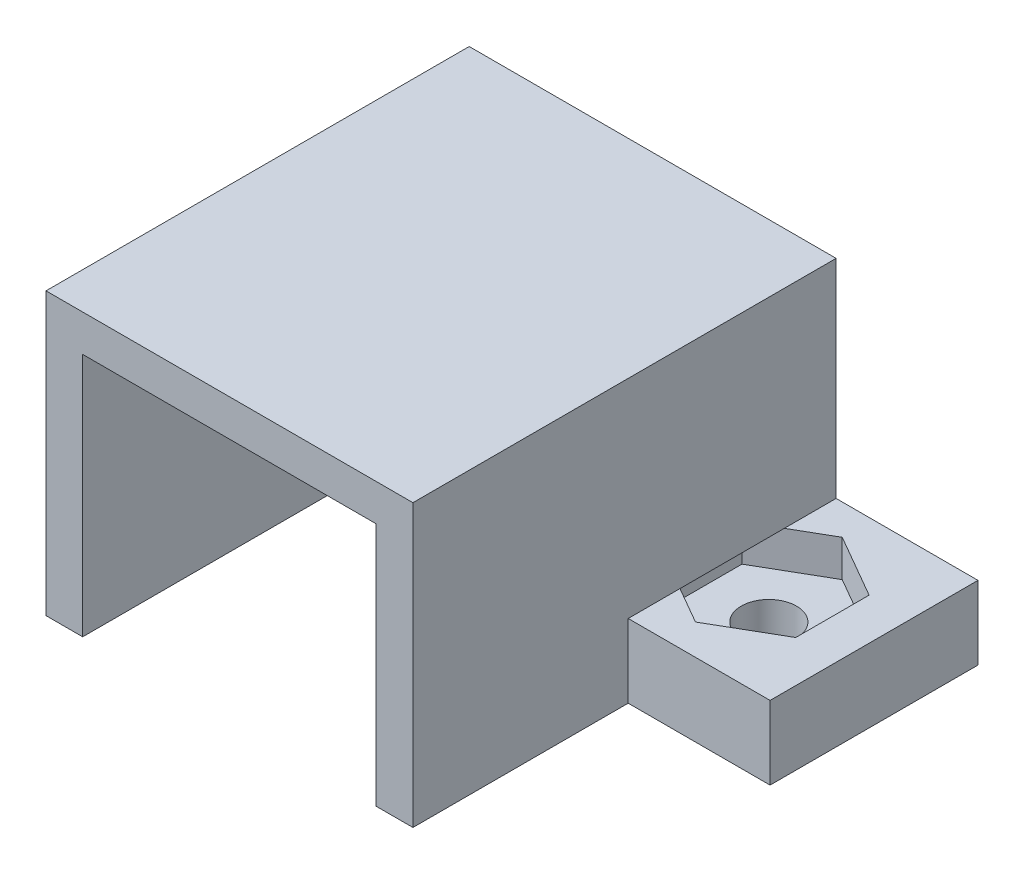
SolidWorks part; units mm, degrees
material "ABS"
ref_plane "Front Plane" through (0, 0, 0) normal (0, 0, 1) x (1, 0, 0)
ref_plane "Top Plane" through (0, 0, 0) normal (0, 1, 0) x (1, 0, 0)
ref_plane "Right Plane" through (0, 0, 0) normal (1, 0, 0) x (0, 0, -1)
sketch "Sketch4" plane through (0, 0, 0) normal (0, 0, 1) x (1, 0, 0)
  line L0 (0, 0) -> (0, 3)
  line L1 (0, 3) -> (5.8, 3)
  line L2 (5.8, 3) -> (5.8, 11.5)
  line L3 (5.8, 11.5) -> (20.8, 11.5)
  line L4 (20.8, 11.5) -> (20.8, 3)
  line L5 (20.8, 3) -> (26.6, 3)
  line L6 (26.6, 3) -> (26.6, 0)
  line L7 (26.6, 0) -> (19.3, 0)
  line L8 (19.3, 0) -> (19.3, 10)
  line L9 (19.3, 10) -> (7.3, 10)
  line L10 (7.3, 10) -> (7.3, 0)
  line L11 (7.3, 0) -> (0, 0)
  dimension "D1" = 5.8
  dimension "D2" = 1.5
  dimension "D3" = 3
  dimension "D4" = 11.5
  dimension "D5" = 1.5
  dimension "D6" = 15
  dimension "D7" = 1.5
extrude "Boss-Extrude4" add sketch "Sketch4" along normal blind 8.5
sketch "Sketch5" plane through (0, 0, 8.5) normal (0, 0, 1) x (1, 0, 0)
  line L0 (7.3, 0) -> (7.3, 10)
  line L1 (7.3, 10) -> (19.3, 10)
  line L2 (19.3, 10) -> (19.3, 0)
  line L3 (19.3, 0) -> (20.8, 0)
  line L4 (19.3, 0) -> (26.6, 0) construction
  line L5 (20.8, 0) -> (20.8, 11.5)
  line L6 (20.8, 11.5) -> (5.8, 11.5)
  line L7 (5.8, 11.5) -> (5.8, 0)
  line L8 (0, 0) -> (7.3, 0) construction
  line L9 (5.8, 0) -> (7.3, 0)
extrude "Boss-Extrude5" add sketch "Sketch5" along normal blind 8.8
sketch "Sketch6" plane through (0, 3, 0) normal (0, 1, 0) x (1, 0, 0)
  line L0 (13.3, 0) -> (13.3, -17.3) construction
  line L1 (20.8, 0) -> (5.8, 0) construction
  line L2 (20.8, -17.3) -> (5.8, -17.3) construction
  line L3 (24.8981, -5.75) -> (22.3, -7.25)
  line L4 (4.3, -7.25) -> (6.8981, -5.75)
  line L5 (6.8981, -5.75) -> (6.8981, -2.75)
  line L6 (6.8981, -2.75) -> (4.3, -1.25)
  line L7 (4.3, -1.25) -> (1.7019, -2.75)
  line L8 (1.7019, -2.75) -> (1.7019, -5.75)
  line L9 (1.7019, -5.75) -> (4.3, -7.25)
  line L10 (24.8981, -2.75) -> (24.8981, -5.75)
  line L11 (22.3, -1.25) -> (24.8981, -2.75)
  line L12 (19.7019, -2.75) -> (22.3, -1.25)
  line L13 (19.7019, -5.75) -> (19.7019, -2.75)
  line L14 (22.3, -7.25) -> (19.7019, -5.75)
  line L15 (5.8, -8.5) -> (0, -8.5) construction
  circle A0 centre (4.3, -4.25) radius 3 construction
  circle A1 centre (22.3, -4.25) radius 3 construction
  dimension "D2" = 6
  dimension "D1" = 9
  dimension "D3" = 4.25
extrude "Cut-Extrude1" cut sketch "Sketch6" against normal blind 1.5
sketch "Sketch7" plane through (0, 1.5, 0) normal (0, 1, 0) x (1, 0, 0)
  line L0 (13.3, 0) -> (13.3, -17.3) construction
  line L1 (20.8, 0) -> (5.8, 0) construction
  line L2 (20.8, -17.3) -> (5.8, -17.3) construction
  line L4 (5.8, -8.5) -> (0, -8.5) construction
  circle A0 centre (4.3, -4.25) radius 1.1303
  circle A1 centre (22.3, -4.25) radius 1.1303
  dimension "D2" = 2.2606
  dimension "D3" = 4.25
  dimension "D1" = 9
extrude "Cut-Extrude2" cut sketch "Sketch7" against normal up to next
